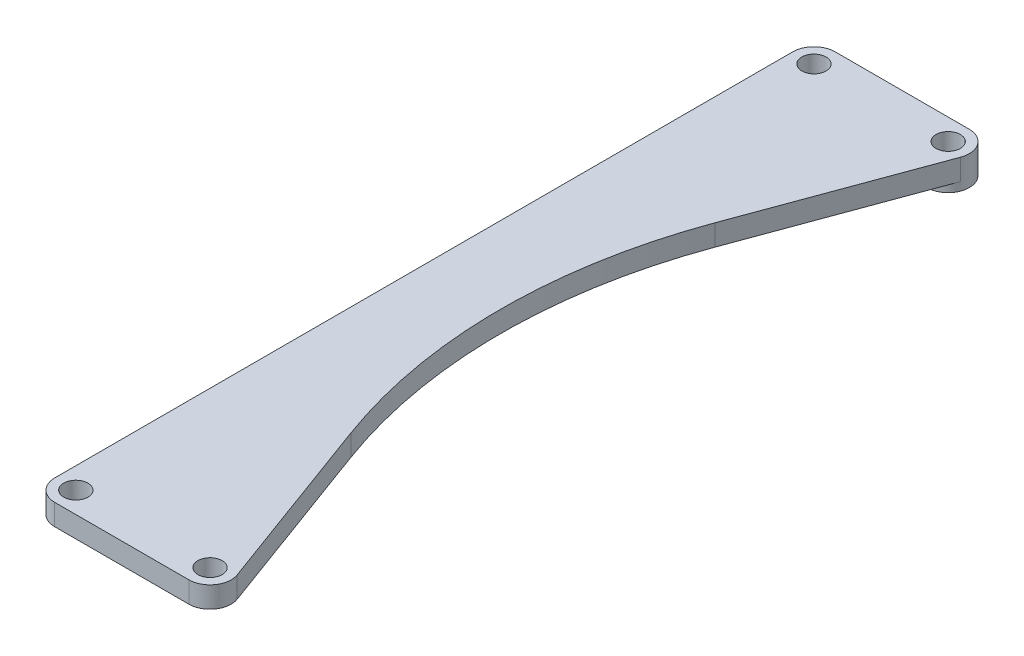
SolidWorks part; units mm, degrees
ref_plane "Front Plane" through (0, 0, 0) normal (0, 0, 1) x (1, 0, 0)
ref_plane "Top Plane" through (0, 0, 0) normal (0, 1, 0) x (1, 0, 0)
ref_plane "Right Plane" through (0, 0, 0) normal (1, 0, 0) x (0, 0, -1)
sketch "Sketch1" plane through (0, 0, 0) normal (0, 1, 0) x (1, 0, 0)
  line L0 (0, 0) -> (25.4, 0) construction
  line L1 (0, 0) -> (0, -139.7) construction
  line L2 (-4, -69.85) -> (4, -69.85) construction
  line L3 (-4, -143.7) -> (-4, 4)
  line L4 (-4, 4) -> (25.4, 4)
  line L5 (-4, -143.7) -> (25.4, -143.7)
  line L6 (4, -69.85) -> (29.1546, -1.3794)
  line L7 (4, -69.85) -> (29.1546, -138.3206)
  circle A0 centre (0, 0) radius 2.3
  circle A1 centre (25.4, 0) radius 2.3
  circle A2 centre (25.4, -139.7) radius 2.3
  circle A3 centre (0, -139.7) radius 2.3
  arc A4 (25.4, -143.7) -> (29.1546, -138.3206) centre (25.4, -139.7) ccw
  arc A5 (29.1546, -1.3794) -> (25.4, 4) centre (25.4, 0) ccw
  point P15 (0, -69.85)
  point P18 (-4, -69.85)
  dimension "D1" = 4.6
  dimension "D8" = 4
  dimension "D4" = 25.4
  dimension "D5" = 139.7
  dimension "D6" = 8
  dimension "D7" = 4
  dimension "D2" = 2
  dimension "D3" = 2
extrude "Boss-Extrude2" add sketch "Sketch1" along normal blind 4
fillet "Fillet1" radius 4 2 edges at (-4, 2, -4) (-4, 2, 143.7)
fillet "Fillet2" radius 100 1 edges at (4, 2, 69.85)
sketch "Sketch2" plane through (0, 4, 0) normal (0, 1, 0) x (1, 0, 0)
  line L0 (0, -4) -> (25.4, -4)
  line L1 (0, 4) -> (25.4, 4)
  arc A0 (0, 4) -> (0, -4) centre (0, 0) ccw
  arc A1 (25.4, -4) -> (25.4, 4) centre (25.4, 0) ccw
  circle A4 centre (0, 0) radius 2.3 construction
  circle A5 centre (25.4, 0) radius 2.3 construction
  circle A6 centre (0, 0) radius 2.3
  circle A7 centre (25.4, 0) radius 2.3
extrude "Boss-Extrude3" add sketch "Sketch2" against normal blind 1.5753 from surface at -4 starting at face at (12.9462, 0, 69.85)
